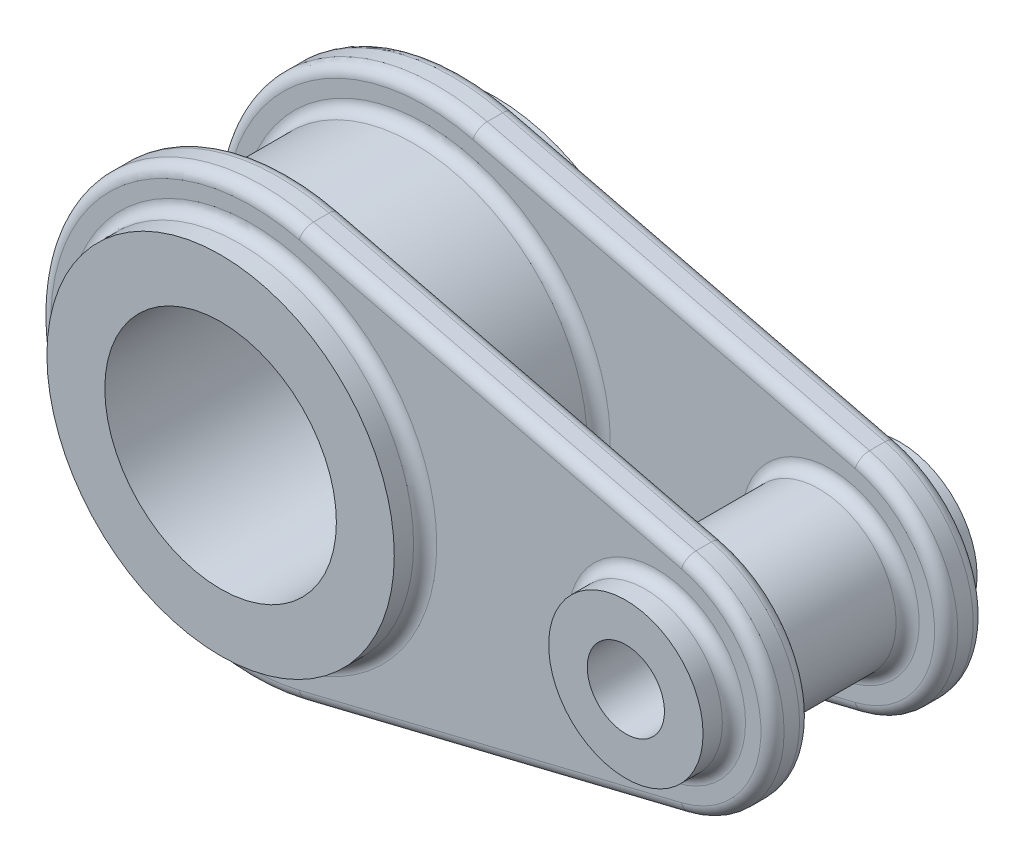
SolidWorks part; units mm, degrees
ref_plane "前视基准面" through (0, 0, 0) normal (0, 0, 1) x (1, 0, 0)
ref_plane "上视基准面" through (0, 0, 0) normal (0, 1, 0) x (1, 0, 0)
ref_plane "右视基准面" through (0, 0, 0) normal (1, 0, 0) x (0, 0, -1)
other "Configuration Table"
sketch "草图1" plane through (0, 0, 0) normal (0, 0, 1) x (1, 0, 0)
  circle A0 centre (0, 0) radius 45
  circle A1 centre (105, 0) radius 20
  dimension "D1" = 90
  dimension "D2" = 40
  dimension "D3" = 105
extrude "凸台-拉伸1" add sketch "草图1" along normal mid plane 71
ref_plane "基准面1" through (0, 0, 17.5) normal (0, 0, 1) x (1, 0, 0)
sketch "草图2" plane through (0, 0, 17.5) normal (0, 0, 1) x (1, 0, 0)
  line L0 (13.0952, 53.4183) -> (112.1429, 29.1373)
  line L1 (13.0952, -53.4183) -> (112.1429, -29.1373)
  arc A0 (13.0952, 53.4183) -> (13.0952, -53.4183) centre (0, 0) ccw
  arc A1 (112.1429, -29.1373) -> (112.1429, 29.1373) centre (105, 0) ccw
  dimension "D1" = 110
  dimension "D2" = 60
extrude "凸台-拉伸2" add sketch "草图2" along normal blind 10
mirror "镜向1" about plane through (0, 0, 0) normal (0, 0, 1) of "凸台-拉伸2"
sketch "草图3" plane through (0, 0, 35.5) normal (0, 0, 1) x (1, 0, 0)
  circle A0 centre (0, 0) radius 30
  circle A1 centre (105, 0) radius 10
  dimension "D1" = 60
  dimension "D2" = 20
extrude "切除-拉伸1" cut sketch "草图3" against normal through all
fillet "圆角1" radius 3 24 edges at (62.619, -41.2778, -27.5) (135, 0, -27.5) (62.619, 41.2778, -27.5) (-55, 0, -27.5) (85, 0, -27.5) (-45, 0, -27.5) (62.619, 41.2778, -17.5) (135, 0, -17.5) (62.619, -41.2778, -17.5) (-55, 0, -17.5) (85, 0, -17.5) (-45, 0, -17.5) (62.619, -41.2778, 17.5) (135, 0, 17.5) (62.619, 41.2778, 17.5) (-55, 0, 17.5) (45, 0, 17.5) (125, 0, 17.5) (62.619, 41.2778, 27.5) (135, 0, 27.5) (62.619, -41.2778, 27.5) (-55, 0, 27.5) (45, 0, 27.5) (125, 0, 27.5)
